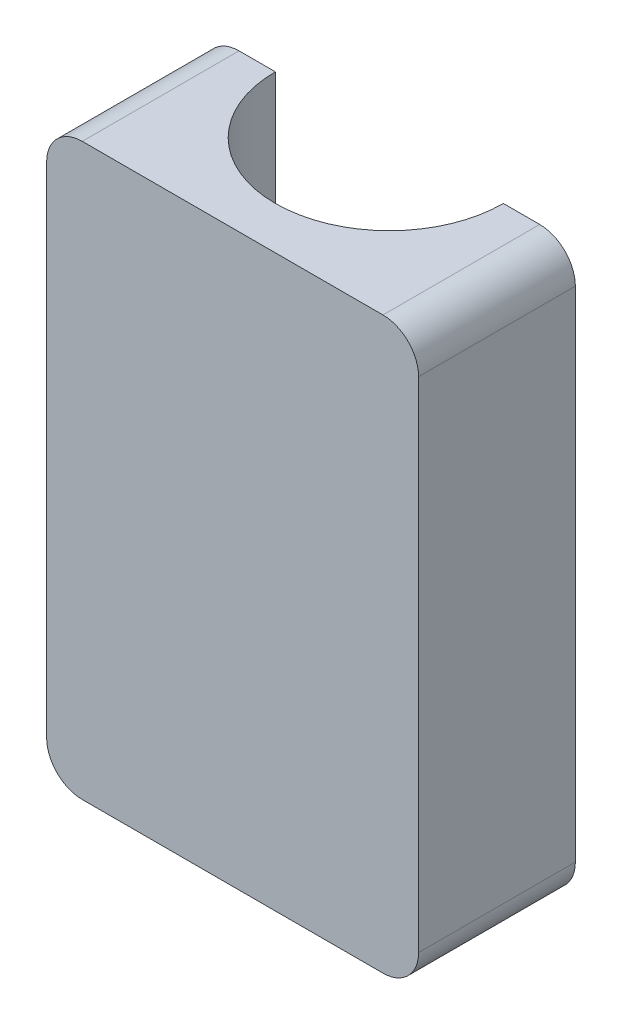
SolidWorks part; units mm, degrees
ref_plane "Plan de face" through (0, 0, 0) normal (0, 0, 1) x (1, 0, 0)
ref_plane "Plan de dessus" through (0, 0, 0) normal (0, 1, 0) x (1, 0, 0)
ref_plane "Plan de droite" through (0, 0, 0) normal (1, 0, 0) x (0, 0, -1)
sketch "Esquisse1" plane through (0, 0, 0) normal (0, 0, 1) x (1, 0, 0)
  line L1 (-41.2248, -2.0065) -> (10.9752, -2.0065)
  line L2 (-41.2248, -2.0065) -> (-41.2248, -82.0065)
  line L3 (-41.2248, -82.0065) -> (10.9752, -82.0065)
  line L4 (10.9752, -2.0065) -> (10.9752, -82.0065)
extrude "Boss.-Extru.2" add sketch "Esquisse1" along normal blind 22
sketch "Esquisse2" plane through (0, -82.0065, 0) normal (0, -1, 0) x (1, 0, 0)
  line L0 (-41.2248, 0) -> (10.9752, 0) construction
  circle A0 centre (-15.1248, 0) radius 16
fillet "Congé2" radius 5 4 edges at (-41.2248, -82.0065, 11) (10.9752, -82.0065, 11) (10.9752, -2.0065, 11) (-41.2248, -2.0065, 11)
extrude "Enlèv. mat.-Extru.3" cut sketch "Esquisse2" against normal through all contours A0
